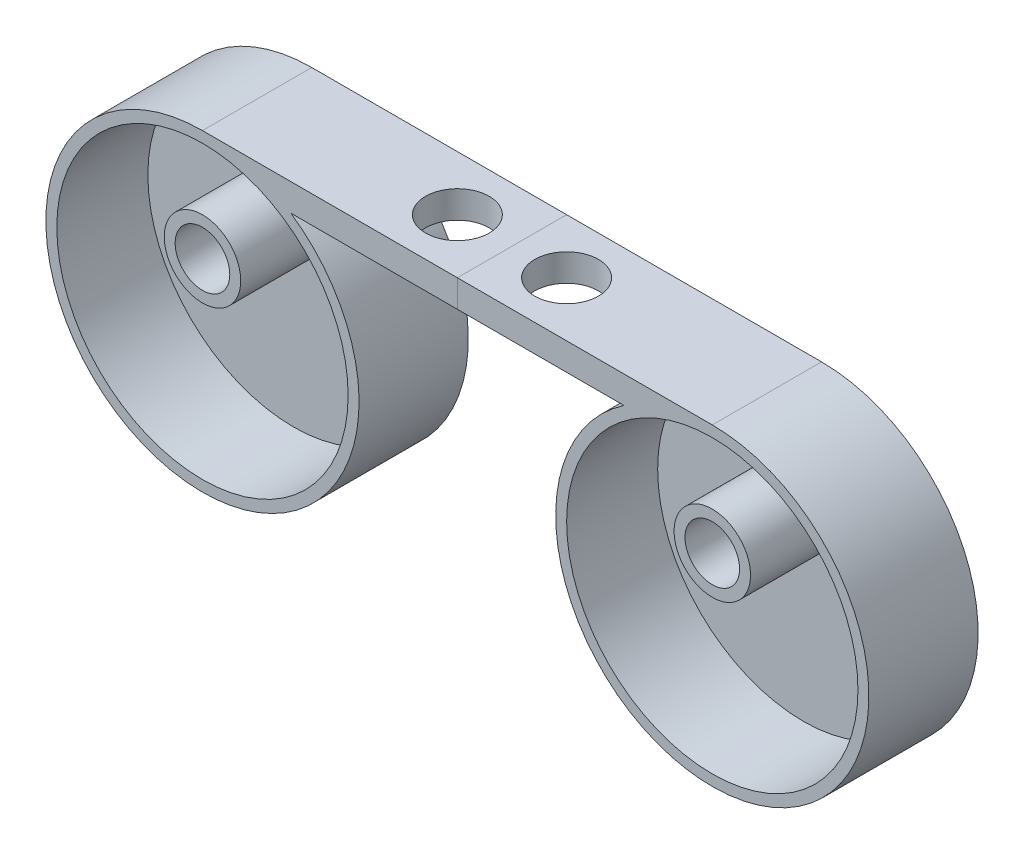
SolidWorks part; units mm, degrees
ref_plane "Front Plane" through (0, 0, 0) normal (0, 0, 1) x (1, 0, 0)
ref_plane "Top Plane" through (0, 0, 0) normal (0, 1, 0) x (1, 0, 0)
ref_plane "Right Plane" through (0, 0, 0) normal (1, 0, 0) x (0, 0, -1)
sketch "Sketch4" plane through (0, 0, 0) normal (0, 0, 1) x (1, 0, 0)
  line L0 (0, 0) -> (0, 17.2) construction
  circle A0 centre (0, 0) radius 17.2
  circle A1 centre (0, 5) radius 3
  dimension "D1" = 34.4
  dimension "D2" = 6
  dimension "D3" = 5
extrude "Boss-Extrude3" add sketch "Sketch4" along normal blind 2
sketch "Sketch5" plane through (0, 0, 2) normal (0, 0, 1) x (1, 0, 0)
  circle A0 centre (0, 0) radius 17.2
  circle A1 centre (0, 0) radius 16
  circle A2 centre (0, 0) radius 17.2 construction
  circle A3 centre (0, 5) radius 3
  circle A4 centre (0, 5) radius 4.2
  circle A5 centre (0, 5) radius 3 construction
  circle M1 centre (0, 0) radius 17.2
  circle M4 centre (0, 5) radius 3
  dimension "D2" = 1.2
  dimension "D1" = 1.2
extrude "Boss-Extrude4" add sketch "Sketch5" along normal blind 10 contours A4 M4 | A1 M1
ref_plane "Plane1" through (28, 0, 0) normal (1, 0, 0) x (0, 0, -1)
sketch "Sketch6" plane through (28, 0, 0) normal (1, 0, 0) x (0, 0, -1)
  line L0 (0, -17.2) -> (0, 17.2) construction
  line L1 (-12, 17.2) -> (0, 17.2)
  line L2 (-12, 17.2) -> (-12, 14.2)
  line L3 (-12, 14.2) -> (0, 14.2)
  line L4 (0, 17.2) -> (0, 14.2)
  dimension "D1" = 3
extrude "Boss-Extrude5" add sketch "Sketch6" against normal up to surface (28 mm away)
sketch "Sketch7" plane through (0, 17.2, 0) normal (0, 1, 0) x (1, 0, 0)
  line L0 (0, 0) -> (28, 0) construction
  line L1 (28, 0) -> (28, -12) construction
  circle A0 centre (22, -6) radius 3.4979
  dimension "D1" = 6
  dimension "D2" = 6
extrude "Cut-Extrude1" cut sketch "Sketch7" against normal up to next
mirror "Mirror1" about plane through (28, 0, 0) normal (1, 0, 0) of bodies 106
